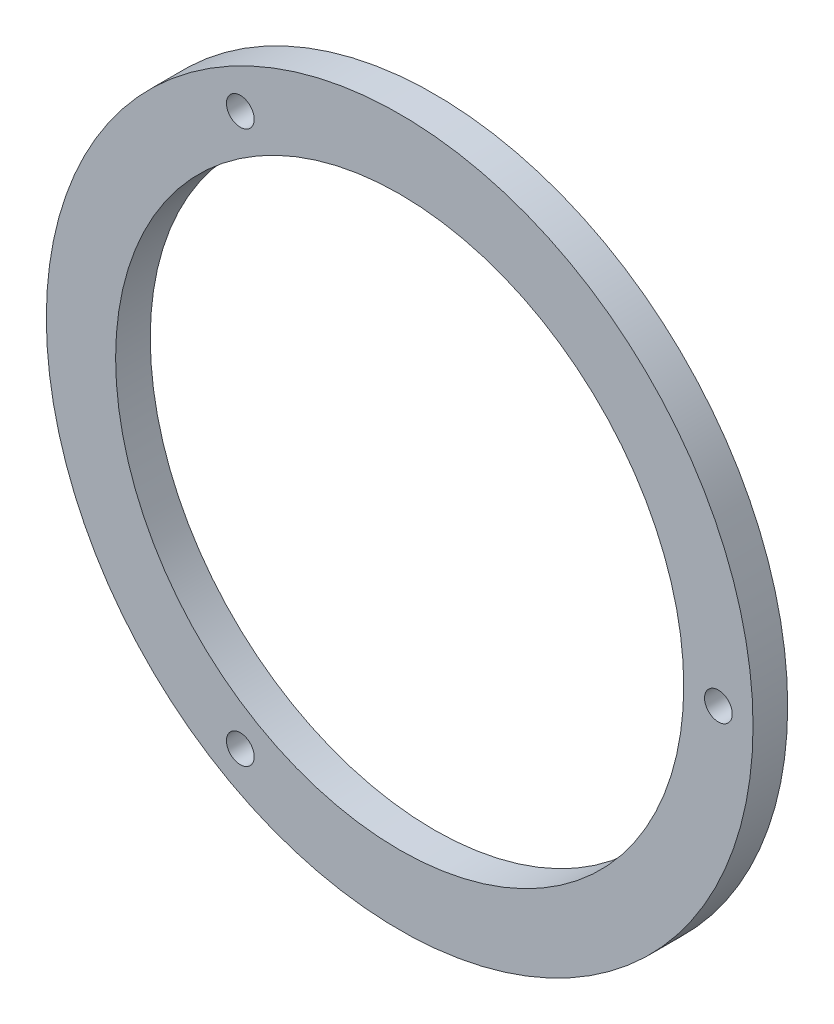
SolidWorks part; units mm, degrees
ref_plane "Plan de face" through (0, 0, 0) normal (0, 0, 1) x (1, 0, 0)
ref_plane "Plan de dessus" through (0, 0, 0) normal (0, 1, 0) x (1, 0, 0)
ref_plane "Plan de droite" through (0, 0, 0) normal (1, 0, 0) x (0, 0, -1)
sketch "Esquisse1" plane through (0, 0, 0) normal (0, 0, 1) x (1, 0, 0)
  line L0 (0, 0) -> (46, 0) construction
  circle A0 centre (46, 0) radius 2
  circle A1 centre (-23, -39.8372) radius 2
  circle A2 centre (-23, 39.8372) radius 2
  circle A3 centre (0, 0) radius 41
  circle A4 centre (0, 0) radius 51
  point P10 (0, 0)
  dimension "D2" = 4
  dimension "D4" = 82
  dimension "D5" = 102
  dimension "D1" = 46
  dimension "D3" = 3
extrude "Boss.-Extru.1" add sketch "Esquisse1" along normal blind 5
